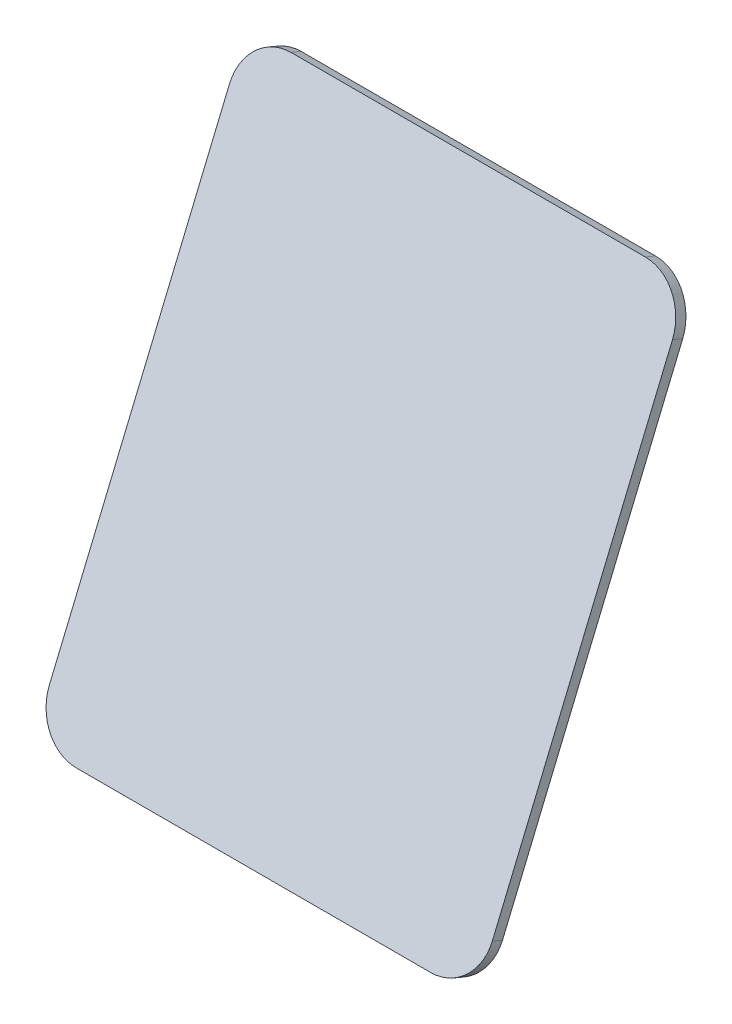
SolidWorks part; units mm, degrees
ref_plane "Front Plane" through (0, 0, 0) normal (0, 0, 1) x (1, 0, 0)
ref_plane "Top Plane" through (0, 0, 0) normal (0, 1, 0) x (1, 0, 0)
ref_plane "Right Plane" through (0, 0, 0) normal (1, 0, 0) x (0, 0, -1)
sketch "Sketch1" plane through (0, 439.6956, 1051.0661) normal (0, 0.3859, 0.9225) x (1, 0, 0)
  line L0 (105.4418, -121.5496) -> (-21.5582, -121.5496) construction
  line L1 (-21.5582, -121.5496) -> (-21.5582, -280.8217) construction
  line L2 (105.4418, -280.8217) -> (-21.5582, -280.8217) construction
  line L3 (105.4418, -121.5496) -> (105.4418, -280.8217) construction
  line L4 (105.4418, -121.5496) -> (-21.5582, -121.5496)
  line L5 (-21.5582, -121.5496) -> (-21.5582, -280.8217)
  line L6 (105.4418, -280.8217) -> (-21.5582, -280.8217)
  line L7 (105.4418, -121.5496) -> (105.4418, -280.8217)
extrude "Boss-Extrude1" add sketch "Sketch1" against normal up to vertex from vertex
fillet "Fillet1" radius 12.7 4 edges at (-21.5582, 328.224, 1099.5568) (-21.5582, 181.2907, 1161.0238) (105.4418, 181.2907, 1161.0238) (105.4418, 328.224, 1099.5568)
